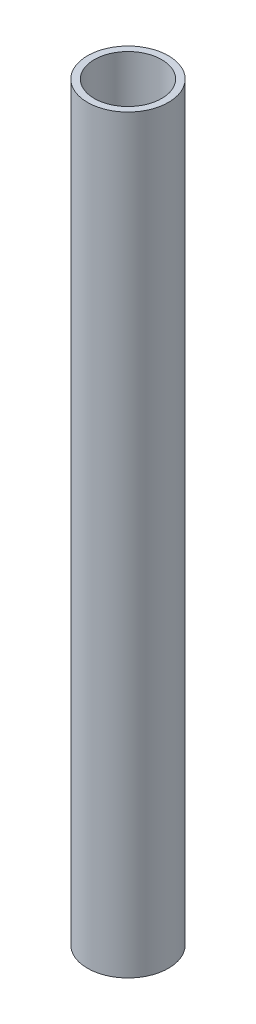
SolidWorks part; units mm, degrees
material "铝青铜"
ref_plane "前视基准面" through (0, 0, 0) normal (0, 0, 1) x (1, 0, 0)
ref_plane "上视基准面" through (0, 0, 0) normal (0, 1, 0) x (1, 0, 0)
ref_plane "右视基准面" through (0, 0, 0) normal (1, 0, 0) x (0, 0, -1)
sketch "草图1" plane through (0, 0, 0) normal (0, 1, 0) x (1, 0, 0)
  circle A0 centre (0, 0) radius 2.5
  circle A1 centre (0, 0) radius 3
extrude "凸台-拉伸1" add sketch "草图1" along normal blind 55.6
